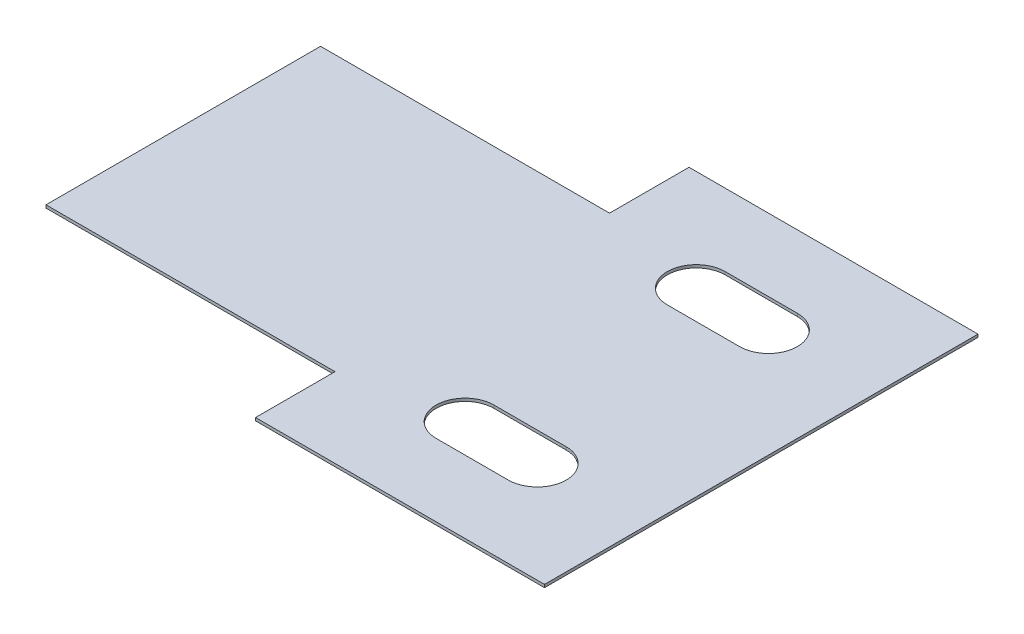
SolidWorks part; units mm, degrees
ref_plane "Front Plane" through (0, 0, 0) normal (0, 0, 1) x (1, 0, 0)
ref_plane "Top Plane" through (0, 0, 0) normal (0, 1, 0) x (1, 0, 0)
ref_plane "Right Plane" through (0, 0, 0) normal (1, 0, 0) x (0, 0, -1)
sketch "Sketch1" plane through (0, 0, 0) normal (0, 1, 0) x (1, 0, 0)
  line L20 (12.4712, 3.9627) -> (9.9712, 3.9627)
  line L21 (9.9712, 1.9627) -> (12.4712, 1.9627)
  line L22 (12.4712, -4.0373) -> (9.9712, -4.0373)
  line L23 (9.9712, -6.0373) -> (12.4712, -6.0373)
  line L24 (-3.7788, -5.7873) -> (6.2212, -5.7873)
  line L25 (6.2212, -5.7873) -> (6.2212, -8.5373)
  line L26 (6.2212, -8.5373) -> (16.2212, -8.5373)
  line L27 (16.2212, -8.5373) -> (16.2212, 6.4627)
  line L28 (16.2212, 6.4627) -> (6.2212, 6.4627)
  line L29 (6.2212, 6.4627) -> (6.2212, 3.7127)
  line L30 (6.2212, 3.7127) -> (-3.7788, 3.7127)
  line L31 (-3.7788, 3.7127) -> (-3.7788, -5.7873)
  arc A4 (9.9712, 3.9627) -> (9.9712, 1.9627) centre (9.9712, 2.9627) ccw
  arc A5 (12.4712, 1.9627) -> (12.4712, 3.9627) centre (12.4712, 2.9627) ccw
  arc A6 (9.9712, -4.0373) -> (9.9712, -6.0373) centre (9.9712, -5.0373) ccw
  arc A7 (12.4712, -6.0373) -> (12.4712, -4.0373) centre (12.4712, -5.0373) ccw
  point P20 (0, 0)
  point P21 (0, 0)
  dimension "D1" = 10
  dimension "D2" = 15
  dimension "D3" = 10
  dimension "D4" = 9.5
  dimension "D5" = 2.5
  dimension "D6" = 6
  dimension "D7" = 3.75
extrude "Boss-Extrude1" add sketch "Sketch1" along normal mid plane 0.1
